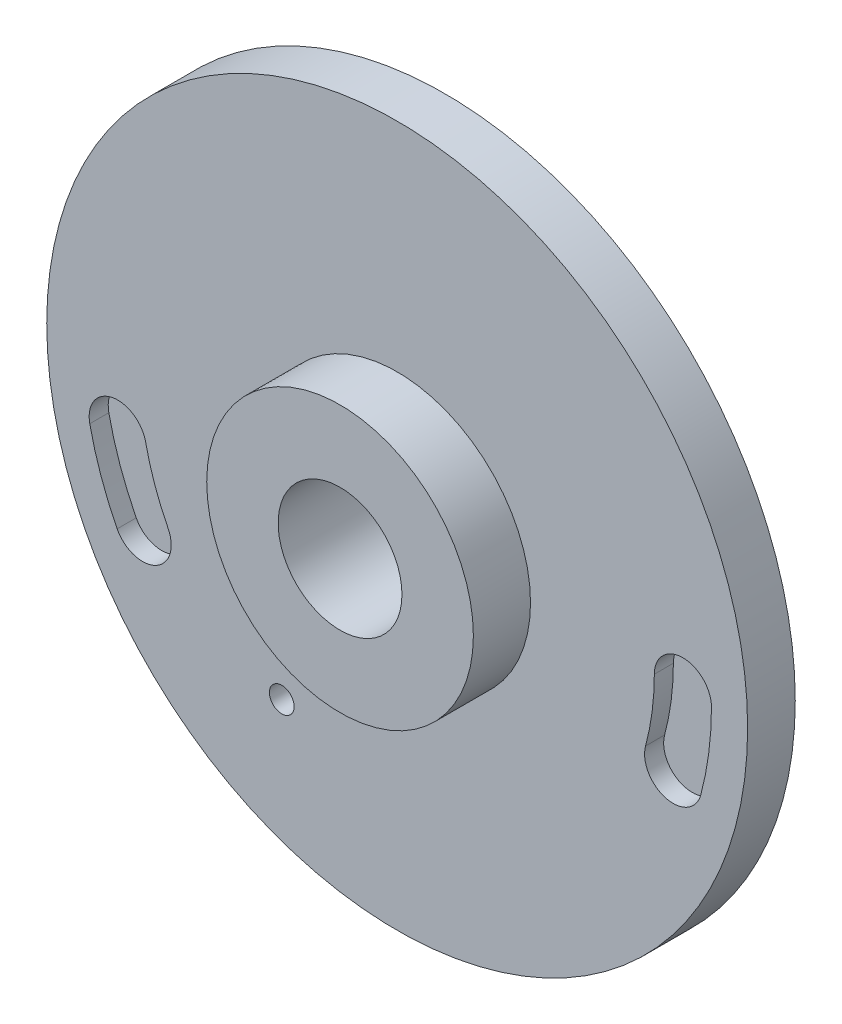
SolidWorks part; units mm, degrees
ref_plane "Front Plane" through (0, 0, 0) normal (0, 0, 1) x (1, 0, 0)
ref_plane "Top Plane" through (0, 0, 0) normal (0, 1, 0) x (1, 0, 0)
ref_plane "Right Plane" through (0, 0, 0) normal (1, 0, 0) x (0, 0, -1)
sketch "Sketch1" plane through (0, 0, 0) normal (0, 0, 1) x (1, 0, 0)
  circle A0 centre (0, 0) radius 36.8
extrude "Boss-Extrude1" add sketch "Sketch1" along normal blind 5
sketch "Sketch7" plane through (0, 0, 5) normal (0, 0, 1) x (1, 0, 0)
  circle A0 centre (0, 0) radius 14
extrude "Boss-Extrude2" add sketch "Sketch7" along normal blind 6
sketch "Sketch2" plane through (0, 0, 11) normal (0, 0, 1) x (1, 0, 0)
  circle A0 centre (0, 0) radius 6.5
extrude "Cut-Extrude1" cut sketch "Sketch2" against normal through all
sketch "Sketch3" plane through (0, 0, 5) normal (0, 0, 1) x (1, 0, 0)
  arc A4 (-26.41, -5.6136) -> (-24.0572, -12.2577) centre (0, 0) ccw
  arc A5 (-32.2789, -6.8611) -> (-29.4032, -14.9817) centre (0, 0) ccw
  arc A6 (-26.41, -5.6136) -> (-32.2789, -6.8611) centre (-29.3444, -6.2374) ccw
  arc A7 (-29.4032, -14.9817) -> (-24.0572, -12.2577) centre (-26.7302, -13.6197) ccw
extrude "Cut-Extrude2" cut sketch "Sketch3" against normal blind 2
sketch "Sketch4" plane through (0, 0, 5) normal (0, 0, 1) x (1, 0, 0)
  arc A4 (26.08, -6.9881) -> (27, 0) centre (0, 0) ccw
  arc A5 (31.8756, -8.541) -> (33, 0) centre (0, 0) ccw
  arc A6 (33, 0) -> (27, 0) centre (30, 0) ccw
  arc A7 (26.08, -6.9881) -> (31.8756, -8.541) centre (28.9778, -7.7646) ccw
extrude "Cut-Extrude3" cut sketch "Sketch4" against normal blind 2
sketch "Sketch5" plane through (0, 0, 5) normal (0, 0, 1) x (1, 0, 0)
  point P4 (-12.1202, -21.8655)
hole_wizard "Tap Drill for M3x0.5 Tap1" positions "Sketch5" profile "Sketch6" hole size "M3x0.5" standard "JIS" end condition up to next
sketch "Sketch6" plane through (-12.1202, -21.8655, 5) normal (1, 0, 0) x (0, -1, 0)
  line L0 (0, 0) -> (0, 5)
  line L1 (0, 5) -> (1.3, 5)
  line L2 (1.3, 5) -> (1.3, 0)
  line L5 (1.3, 0) -> (0, 0)
  line L11 (0, -6.35) -> (0, 107.95) construction
  dimension "Thru Hole Dia." = 2.6
  dimension "Thru Hole Depth" = 5
